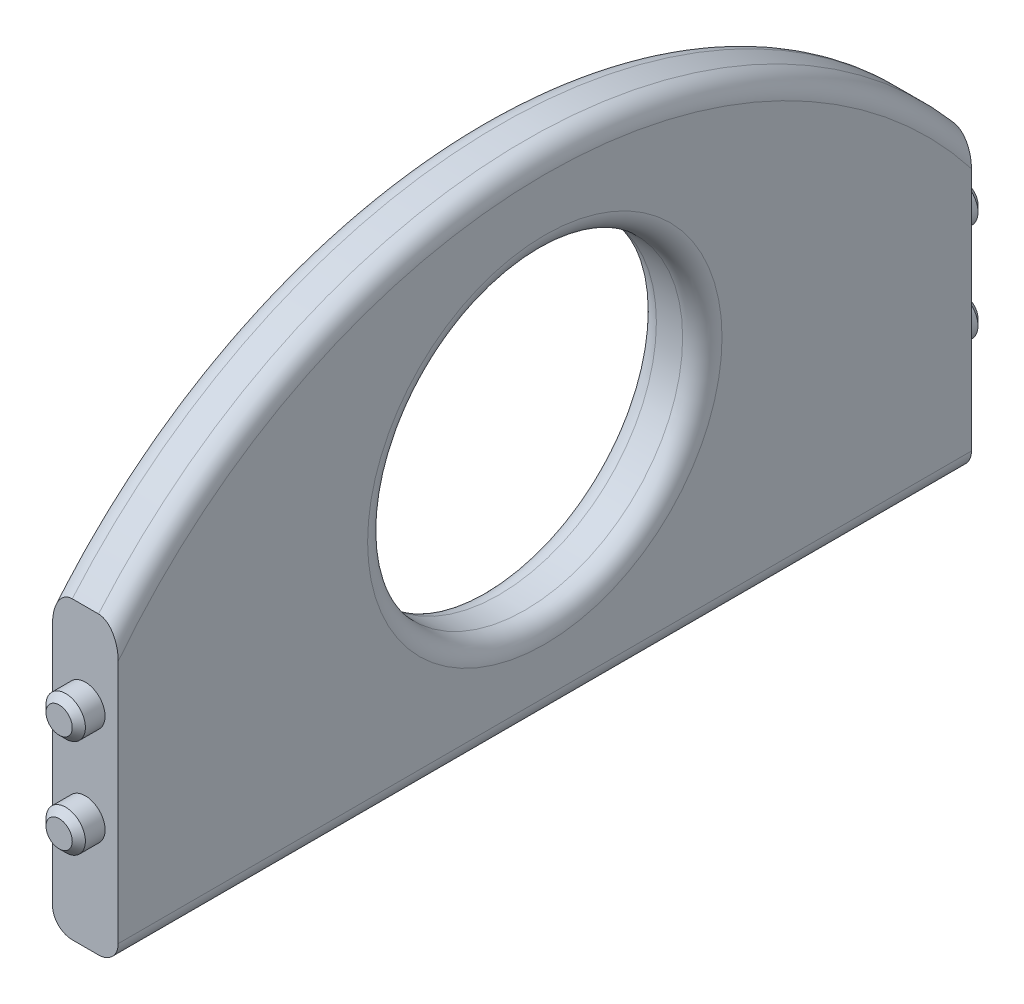
SolidWorks part; units mm, degrees
ref_plane "前基準面" through (0, 0, 0) normal (0, 0, 1) x (1, 0, 0)
ref_plane "上基準面" through (0, 0, 0) normal (0, 1, 0) x (1, 0, 0)
ref_plane "右基準面" through (0, 0, 0) normal (1, 0, 0) x (0, 0, -1)
sketch "草圖1" plane through (0, 0, 0) normal (1, 0, 0) x (0, 0, -1)
  line L0 (0, 0) -> (0, 37) construction
  line L1 (-65, 45) -> (65, 45) construction
  line L2 (-65, 45) -> (-65, 0)
  line L3 (-65, 0) -> (65, 0)
  line L4 (65, 45) -> (65, 0)
  arc A0 (-65, 45) -> (65, 45) centre (0, -10.4167) cw
  circle A1 centre (0, 37) radius 24
  dimension "D3" = 48
  dimension "D4" = 37
  dimension "D1" = 130
  dimension "D2" = 45
  dimension "D5" = 75
extrude "伸長1" add sketch "草圖1" along normal mid plane 10
sketch "草圖2" plane through (0, 0, 65) normal (0, 0, 1) x (1, 0, 0)
  line L0 (0, 0) -> (0, 32) construction
  line L1 (5, 0) -> (-5, 0) construction
  circle A0 centre (0, 32) radius 3
  circle A1 centre (0, 17) radius 3
  dimension "D1" = 6
  dimension "D2" = 15
  dimension "D3" = 17
extrude "伸長2" add sketch "草圖2" along normal blind 4
chamfer "導角1" distance 1 angle 45 2 edges at (3, 17, 69) (3, 32, 69)
mirror "鏡射1" about plane through (0, 0, 0) normal (0, 0, 1) of "導角1", "伸長2"
fillet "圓角1" radius 3 6 edges at (-5, 37, -24) (5, 37, -24) (-5, 0, 0) (5, 0, 0) (-5, 75, 0) (5, 75, 0)
